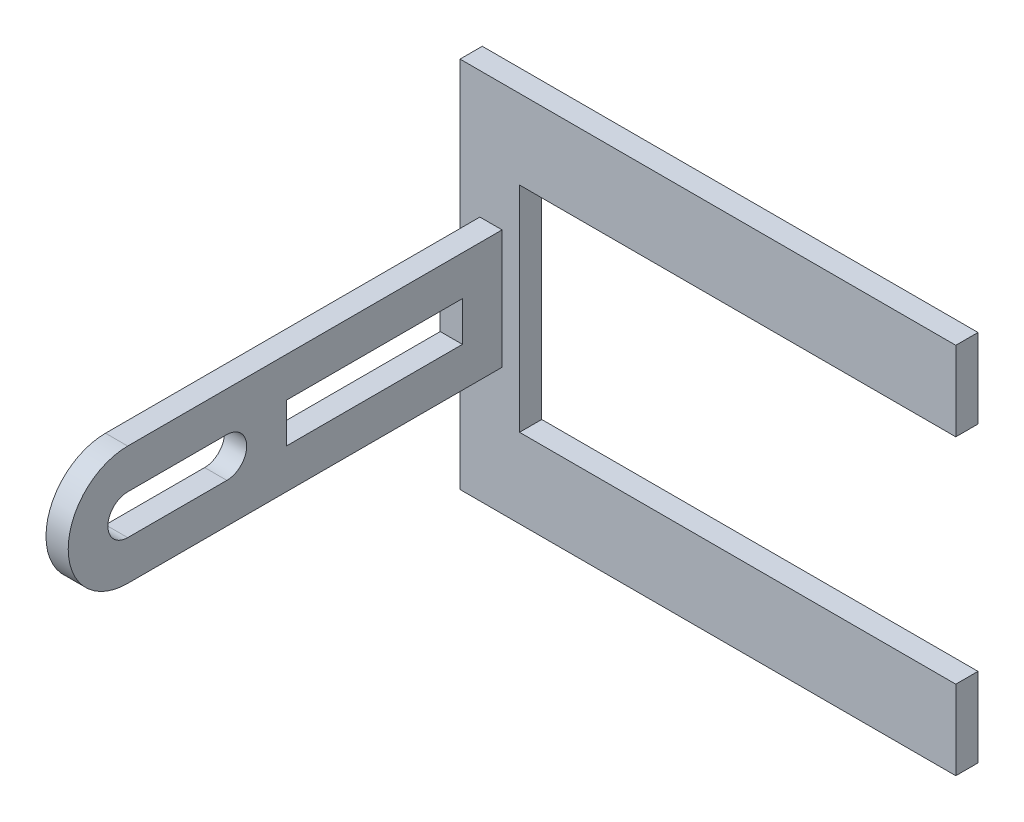
SolidWorks part; units mm, degrees
ref_plane "Front Plane" through (0, 0, 0) normal (0, 0, 1) x (1, 0, 0)
ref_plane "Top Plane" through (0, 0, 0) normal (0, 1, 0) x (1, 0, 0)
ref_plane "Right Plane" through (0, 0, 0) normal (1, 0, 0) x (0, 0, -1)
sketch "Sketch1" plane through (0, 0, 0) normal (0, 0, 1) x (1, 0, 0)
  line L0 (30, 13.5) -> (30, 23.5)
  line L1 (30, 23.5) -> (-32.5, 23.5)
  line L2 (-32.5, 23.5) -> (-32.5, -23.5)
  line L3 (-32.5, -23.5) -> (30, -23.5)
  line L4 (30, -23.5) -> (30, -13.5)
  line L5 (30, -13.5) -> (-25, -13.5)
  line L6 (-25, -13.5) -> (-25, 13.5)
  line L7 (-25, 13.5) -> (30, 13.5)
  point P6 (-25, 0)
  dimension "D1" = 10
  dimension "D2" = 27
  dimension "D3" = 10
  dimension "D4" = 30
  dimension "D5" = 25
  dimension "D6" = 7.5
extrude "Boss-Extrude1" add sketch "Sketch1" along normal blind 2.8
ref_plane "Plane1" through (-30, 0, 0) normal (1, 0, 0) x (0, 0, -1)
sketch "Sketch2" plane through (-30, 0, 0) normal (1, 0, 0) x (0, 0, -1)
  line L0 (-2.8, -7.5) -> (-2.8, 7.5)
  line L1 (-2.8, 7.5) -> (-50, 7.5)
  line L3 (-50, -7.5) -> (-2.8, -7.5)
  line L4 (-50, -2.5) -> (-37.5, -2.5)
  line L11 (-2.8, 13.5) -> (-2.8, 23.5) construction
  line L12 (-7.8, -2.5) -> (-7.8, 2.5)
  line L13 (-7.8, 2.5) -> (-30, 2.5)
  line L14 (-30, 2.5) -> (-30, -2.5)
  line L15 (-37.5, 2.5) -> (-50, 2.5)
  line L17 (-30, -2.5) -> (-7.8, -2.5)
  line L18 (-7.8, 2.5) -> (-50, 2.5) construction
  line L19 (0, -13.5) -> (0, 13.5) construction
  line L20 (-50, -2.5) -> (-7.8, -2.5) construction
  arc A0 (-50, 7.5) -> (-50, -7.5) centre (-50, 0) ccw
  arc A3 (-50, 2.5) -> (-50, -2.5) centre (-50, 0) ccw
  arc A4 (-37.5, 2.5) -> (-37.5, -2.5) centre (-37.5, 0) cw
  point P22 (-2.8, 0)
  dimension "D2" = 12.5
  dimension "D5" = 7.5
  dimension "D1" = 5
  dimension "D3" = 7.5
  dimension "D4" = 50
extrude "Boss-Extrude2" add sketch "Sketch2" along normal blind 2.8
